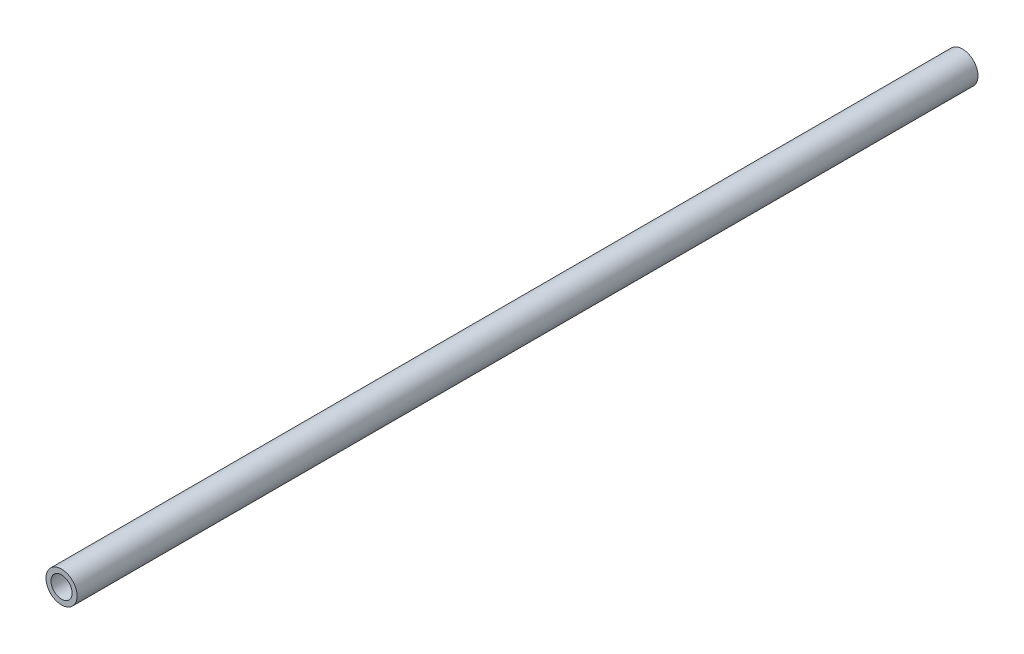
SolidWorks part; units mm, degrees
material "ABS PC"
ref_plane "Front Plane" through (0, 0, 0) normal (0, 0, 1) x (1, 0, 0)
ref_plane "Top Plane" through (0, 0, 0) normal (0, 1, 0) x (1, 0, 0)
ref_plane "Right Plane" through (0, 0, 0) normal (1, 0, 0) x (0, 0, -1)
sketch "Sketch1" plane through (0, 0, 0) normal (0, 0, 1) x (1, 0, 0)
  circle A0 centre (-100, 100) radius 4.6636
  circle A1 centre (-100, 100) radius 3.1636
  dimension "D1" = 1.5
extrude "Boss-Extrude1" add sketch "Sketch1" along normal blind 30 and the other way blind 240 contours A0 A1
